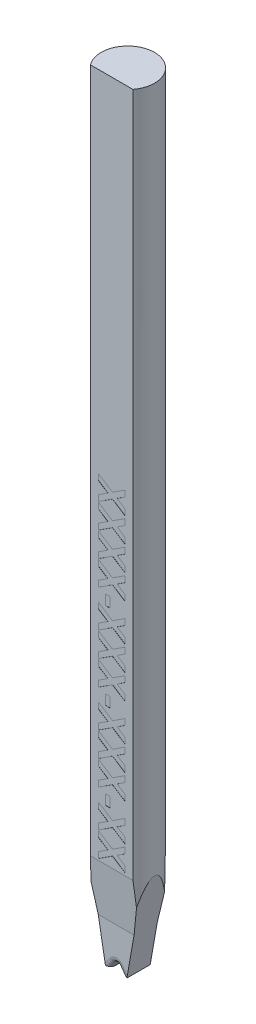
SolidWorks part; units mm, degrees
ref_plane "Ebene vorne" through (0, 0, 0) normal (0, 0, 1) x (1, 0, 0)
ref_plane "Ebene oben" through (0, 0, 0) normal (0, 1, 0) x (1, 0, 0)
ref_plane "Ebene rechts" through (0, 0, 0) normal (1, 0, 0) x (0, 0, -1)
sketch "sketch_TL_cutting" plane through (0, 0, 0) normal (0, 1, 0) x (1, 0, 0)
  circle A0 centre (0, 0) radius 0.9969
extrude "TL_cutting" add sketch "sketch_TL_cutting" along normal blind 29.0068
sketch "sketch_TDF_grinding" plane through (0, 0, 0) normal (0, 1, 0) x (1, 0, 0)
  line L0 (0, 0) -> (0, -0.6033) construction
  line L1 (-1.007, -2.6171) -> (1.007, -2.6171)
  line L2 (-1.007, -2.6171) -> (-1.007, -0.6033)
  line L3 (-1.007, -0.6033) -> (1.007, -0.6032)
  line L4 (1.007, -2.6171) -> (1.007, -0.6032)
  circle A1 centre (0, 0) radius 0.9969 construction
  point P9 (0, -2.6172)
  dimension "TD_2Offset_X" = 2.0139
  dimension "TD_2Offset_Z" = 2.0139
extrude "TDF_grinding" cut sketch "sketch_TDF_grinding" along normal through all
sketch "sketch_engraving" plane through (0, 0, 0.6033) normal (0, 0, 1) x (1, 0, 0)
  line L0 (0.7937, 29.0068) -> (-0.7937, 29.0068) construction
  line L6 (-0.7937, 0) -> (0.7937, 0) construction
  line L7 (0, 0) -> (0, 15.9537) construction
  line L8 (-0.5, 15.9537) -> (-0.5, 0) construction
  text T0 "XXXX-XXX-XXX-XX" font "Arial" height 1
  dimension "D2" = 0.5
  dimension "EngravingStart" = 13.0531
extrude "engraving" cut sketch "sketch_engraving" against normal blind 0.005
sketch "sketch_VW_VR_grinding" plane through (0, 0, 0) normal (0, 0, 1) x (1, 0, 0)
  line L0 (-0.9919, -0.01) -> (-0.9919, 1.509)
  line L1 (0.9919, -0.01) -> (0.9919, 1.509)
  line L2 (-0.9919, 0) -> (0.9919, 0) construction
  line L3 (-1.007, 1.514) -> (-0.9969, 1.514)
  line L4 (0.9969, 1.514) -> (1.007, 1.514)
  line L5 (-1.007, 1.514) -> (-1.007, -0.01)
  line L6 (-1.007, -0.01) -> (-0.9919, -0.01)
  line L7 (0.9919, -0.01) -> (1.007, -0.01)
  line L8 (1.007, -0.01) -> (1.007, 1.514)
  line L9 (-0.9969, 1.514) -> (-0.9969, 1.509) construction
  line L10 (-0.9919, 1.509) -> (-0.9969, 1.509) construction
  line L11 (0.9919, 1.509) -> (0.9969, 1.509) construction
  line L12 (0.9969, 1.514) -> (0.9969, 1.509) construction
  arc A0 (-0.9969, 1.514) -> (-0.9919, 1.509) centre (-0.9969, 1.509) cw
  arc A2 (0.9919, 1.509) -> (0.9969, 1.514) centre (0.9969, 1.509) cw
  dimension "D1" = 0.01
  dimension "D4" = 2.0139
extrude "VW_VR_grinding" cut sketch "sketch_VW_VR_grinding" against normal blind 1.007 and the other way blind 1.007
sketch "sketch_ISA_grinding" plane through (0, 0, 0) normal (0, 0, 1) x (1, 0, 0)
  line L0 (-0.4001, 0) -> (-1.007, 3.4419)
  line L4 (1.007, 3.4419) -> (0.4001, 0)
  line L5 (0.4001, 0) -> (-0.4001, 0)
  line L6 (0, 0) -> (0, 30.49) construction
  line L7 (-1.007, 3.4419) -> (-1.007, -0.01)
  line L12 (-1.007, -0.01) -> (1.007, -0.01)
  line L13 (1.007, -0.01) -> (1.007, 3.4419)
  line L14 (-0.9919, -0.01) -> (-0.9919, 1.509) construction
  point P3 (-0.9919, 3.3568)
  dimension "ISA" = 20
  dimension "TD_2Offset" = 2.0139
  dimension "Offset" = 0.01
extrude "ISA_grinding" cut sketch "sketch_ISA_grinding" against normal blind 1.007 and the other way blind 1.007
sketch "sketch_pre_FRX_BRX" plane through (0, 0, 0) normal (1, 0, 0) x (0, 0, -1)
  line L0 (0.9969, -0.01) -> (0.9969, 3.9152) construction
  line L1 (-0.6033, -0.01) -> (-0.6033, 1.514) construction
  line L2 (-0.4356, -0.01) -> (-0.4356, 1.514)
  line L3 (-0.4356, 1.514) -> (-1.007, 1.514)
  line L4 (-1.007, 1.514) -> (-1.007, -0.01)
  line L5 (-1.007, -0.01) -> (-0.4356, -0.01)
  line L6 (0.4356, -0.01) -> (0.4356, 1.514)
  line L7 (0.4356, 1.514) -> (1.0069, 1.514)
  line L8 (1.0069, 1.514) -> (1.007, -0.01)
  line L9 (1.007, -0.01) -> (0.4356, -0.01)
  dimension "D3" = 0.01
  dimension "D4" = 1.524
  dimension "D5" = 2.0139
  dimension "D6" = 0.8712
  dimension "D2" = 0.01
  dimension "D7" = 1.4326
extrude "pre_FRX_BRX" cut sketch "sketch_pre_FRX_BRX" against normal blind 1.007 and the other way blind 1.007
sketch "sketch_contour_V-Groove" plane through (0, 0, 0) normal (1, 0, 0) x (0, 0, -1)
  line L0 (-0.6033, 0.254) -> (0, 0.254)
  line L1 (0, 0.254) -> (0.9969, 0.254)
  line L2 (0.9969, -0.8411) -> (0.9969, 1.3178) construction
  line L3 (-0.6033, -0.9209) -> (-0.6033, 1.9363) construction
  line L4 (-0.6033, 0) -> (0.997, 0) construction
  line L5 (0.4356, 0) -> (0.4356, 0.254) construction
  line L6 (-0.4356, 0) -> (-0.4356, 0.254) construction
  dimension "D1" = 0
ref_plane "front" through (0, 0, 0.6033) normal (0, 0, 1) x (1, 0, 0)
ref_plane "back" through (0, 0, -0.9969) normal (0, 0, 1) x (1, 0, 0)
sketch "sketch_section_V-Groove" plane through (0, 0, 0.6033) normal (0, 0, 1) x (1, 0, 0)
  line L0 (-1.9982, -2.54) -> (-0.0659, 0.2197)
  line L2 (0.0659, 0.2197) -> (1.9982, -2.54)
  line L3 (-1.9982, -2.54) -> (1.9982, -2.54)
  line L4 (0, -2.54) -> (0, 0.254) construction
  line L5 (-0.2197, 0) -> (0.2197, 0) construction
  arc A0 (0.0659, 0.2197) -> (-0.0659, 0.2197) centre (0, 0.1736) ccw
  dimension "GA" = 70
sweep "V-Groove_EDM" cut profiles "sketch_section_V-Groove" path "sketch_contour_V-Groove"
fillet "FR_EDM" radius 0.2007 3 edges at (0.1428, 0.1099, 0.4356) (0, 0.254, 0.4356) (-0.1428, 0.1099, 0.4356)
fillet "BR_EDM" radius 0.2007 3 edges at (0.1428, 0.1099, -0.4356) (0, 0.254, -0.4356) (-0.1428, 0.1099, -0.4356)
sketch "sketch_FA_BA_grinding" plane through (0, 0, 0) normal (1, 0, 0) x (0, 0, -1)
  line L2 (1.9969, 19.3702) -> (1.997, -0.1)
  line L3 (1.997, -0.1) -> (0.4356, -0.1)
  line L5 (0.4356, -0.1) -> (0.4356, 1.524)
  line L6 (0.4356, 1.524) -> (1.9969, 19.3702)
  line L7 (0.9969, -0.1) -> (0.9969, 7.9401) construction
  line L8 (-0.6032, 3.4401) -> (-0.6032, -0.1) construction
  line L9 (-2.2816, 22.6236) -> (-0.4356, 1.524)
  line L10 (-0.4356, 1.524) -> (-0.4356, -0.1)
  line L11 (-0.4356, -0.1) -> (-2.2816, -0.1)
  line L12 (-2.2816, -0.1) -> (-2.2816, 22.6236)
  line L13 (-0.4356, 1.524) -> (0.4356, 1.524) construction
  dimension "D4" = 1
  dimension "D1" = 0.1
  dimension "FA" = 5
  dimension "BA" = 5
extrude "FA_BA_grinding" cut sketch "sketch_FA_BA_grinding" against normal blind 1.007 and the other way blind 1.007
sketch "sketch_groove_dimensions" plane through (0, 0, 0) normal (1, 0, 0) x (0, 0, -1)
  line L0 (-0.235, 0.254) -> (0.235, 0.254)
  line L1 (-0.4356, 0) -> (-0.4356, 0.4547) construction
  line L2 (0.9969, 0) -> (0.9969, 0.4166) construction
  line L3 (0.4356, 0) -> (0.4356, 0.4547) construction
  line L4 (-0.6033, 0) -> (-0.6033, 0.3999) construction
  arc A0 (0.235, 0.254) -> (0.4356, 0.4547) centre (0.235, 0.4547) ccw
  arc A1 (-0.235, 0.254) -> (-0.4356, 0.4547) centre (-0.235, 0.4547) cw
equation "\"_Offset\"=0.01mm"
equation "\"TL\"=29.0068mm"
equation "\"TD\"=1.9939mm"
equation "\"TDF\"=1.6002mm"
equation "\"BA\"=5deg"
equation "\"ISA\"=20deg"
equation "\"FA\"=5deg"
equation "\"GR\"=0.08128mm"
equation "\"GA\"=70deg"
equation "\"GD\"=0.254mm"
equation "\"FL\"=0.87122mm"
equation "\"F\"=0.4699mm"
equation "\"FX\"=0.16764mm"
equation "\"B\"=0.43942mm"
equation "\"VW\"=0mm"
equation "\"cleaned_VR\"= IIF ( \"VR\" > 0 , \"VR\" , \"E\" - \"_Offset\" )"
equation "\"cleaned_VW\"= IIF ( \"VW\" > 0 , \"VW\" , \"TD\" - \"_Offset\" )"
equation "\"back_edge\"= \"TD\" / 2 - \"X\""
equation "\"side_edge_Offset\"= \"TD\" / 2 + \"_Offset\""
equation "\"TD@sketch_TL_cutting\"=\"TD\""
equation "\"TL@TL_cutting\"=\"TL\""
equation "\"TDF@sketch_TDF_grinding\"=\"TDF\""
equation "\"TD_2Offset_X@sketch_TDF_grinding\"=\"TD\"+2*\"_Offset\""
equation "\"TD_2Offset_Z@sketch_TDF_grinding\"=\"TD\"+2*\"_Offset\""
equation "\"TL_Offset\"= \"TL\" + \"_Offset\""
equation "\"ISA@sketch_ISA_grinding\"=\"ISA\""
equation "\"W@sketch_ISA_grinding\"=\"W\""
equation "\"TD_2Offset@sketch_ISA_grinding\"=\"TD\"+2*\"_Offset\""
equation "\"Offset@sketch_ISA_grinding\"=\"_Offset\""
equation "\"05TD_Offset_posZ@ISA_grinding\"=\"side_edge_Offset\""
equation "\"05TD_Offset_negZ@ISA_grinding\"=\"side_edge_Offset\""
equation "\"E\"=1.524mm"
equation "\"cleaned_X\"= IIF ( \"X\" > 0 , \"X\" , \"TD\" / 2 - \"FL\" / 2 )"
equation "\"FR\"=0.20066mm"
equation "\"BR\"=0.20066mm"
equation "\"D1\"= \"side_edge_Offset\""
equation "\"D2\"= \"side_edge_Offset\""
equation "\"TDF@sketch_FA_BA_grinding\" = \"TDF\""
equation "\"FL@sketch_FA_BA_grinding\"=\"FL\""
equation "\"E@sketch_FA_BA_grinding\" = \"E\""
equation "\"D1@FA_BA_grinding\"=\"side_edge_Offset\""
equation "\"D2@FA_BA_grinding\"=\"side_angle_Offset\""
equation "\"10GD@sketch_section_V-Groove\" = 10 * \"GD\""
equation "\"GA@sketch_section_V-Groove\" = \"GA\""
equation "\"GD@sketch_section_V-Groove\" = \"GD\""
equation "\"B@sketch_section_V-Groove\" = \"B\""
equation "\"GD@sketch_contour_V-Groove\" = \"GD\""
equation "\"cleaned_FRX\"= IIF ( \"FRX\" > 0 , \"FRX\" , \"FR\" )"
equation "\"cleaned_BRX\"= IIF ( \"BRX\" > 0 , \"BRX\" , \"BR\" )"
equation "\"FL_groove_angle\"=0deg"
equation "\"D3@sketch_pre_FRX_BRX\" = \"_Offset\""
equation "\"D4@sketch_pre_FRX_BRX\" = \"E\""
equation "\"D5@sketch_pre_FRX_BRX\" = 2 * \"side_edge_Offset\""
equation "\"D6@sketch_pre_FRX_BRX\" = \"FL\" + ( \"FR\" - \"cleaned_FRX\" ) + ( \"BR\" - \"cleaned_BRX\" )"
equation "\"TD/2@sketch_pre_FRX_BRX\" = \"TD\" / 2"
equation "\"TDF@sketch_pre_FRX_BRX\" = \"TDF\""
equation "\"D2@sketch_pre_FRX_BRX\" = \"_Offset\""
equation "\"D1@pre_FRX_BRX\" = \"side_edge_Offset\""
equation "\"D2@pre_FRX_BRX\" = \"side_edge_Offset\""
equation "\"D1@BR_EDM\"=\"BR\""
equation "\"TD/2@sketch_FA_BA_grinding\" = \"TD\" / 2"
equation "\"TD/2@sketch_contour_V-Groove\" = \"TD\" / 2"
equation "\"TDF@sketch_contour_V-Groove\" = \"TDF\""
equation "\"D1@sketch_contour_V-Groove\"=\"FL_groove_angle\""
equation "\"FL@sketch_contour_V-Groove\"=\"FL\""
equation "\"FL/2@sketch_contour_V-Groove\" = \"FL\" / 2"
equation "\"D1@FR_EDM\"=\"FR\""
equation "\"D1@sketch_VW_VR_grinding\" = \"_Offset\""
equation "\"D4@sketch_VW_VR_grinding\" = 2 * \"side_edge_Offset\""
equation "\"VR@sketch_VW_VR_grinding\" = \"cleaned_VR\""
equation "\"VW@sketch_VW_VR_grinding\"=\"cleaned_VW\""
equation "\"D1@VW_VR_grinding\" = \"side_edge_Offset\""
equation "\"D2@VW_VR_grinding\" = \"side_edge_Offset\""
equation "\"X\"=0mm"
equation "\"VR\"=0mm"
equation "\"W\"=0.8001mm"
equation "\"VW_radius\"= \"cleaned_VW\" / 10"
equation "\"VW_radius_cleaned\"= IIF ( \"VW\" > 0 , \"VW_radius\" , \"_Offset\" / 2 )"
equation "\"D2@sketch_VW_VR_grinding\"=\"VW_radius_cleaned\""
equation "\"FRX\"=0mm"
equation "\"BRX\"=0mm"
equation "\"FA@sketch_FA_BA_grinding\" = \"FA\""
equation "\"D4@sketch_FA_BA_grinding\"=\"_Offset\"*100"
equation "\"BA@sketch_FA_BA_grinding\" = \"BA\""
equation "\"D1@sketch_groove_dimensions\" = \"TD\" / 2"
equation "\"FL@sketch_groove_dimensions\" = \"FL\""
equation "\"FR@sketch_groove_dimensions\" = \"FR\""
equation "\"BR@sketch_groove_dimensions\" = \"BR\""
equation "\"FRX@sketch_groove_dimensions\" = \"cleaned_FRX\""
equation "\"BRX@sketch_groove_dimensions\" = \"cleaned_BRX\""
equation "\"GD@sketch_groove_dimensions\" = \"GD\""
equation "\"cleaned_FX\"= IIF ( \"FX\" > 0 , \"FX\" , \"TDF\" - ( \"TD\" + \"FL\" ) / 2 )"
equation "\"D7@sketch_pre_FRX_BRX\"=\"TDF\"-\"cleaned_FX\"-(\"FR\"-\"cleaned_FRX\")"
equation "\"FX@sketch_contour_V-Groove\" = \"cleaned_FX\""
equation "\"FX@sketch_FA_BA_grinding\" = \"cleaned_FX\""
equation "\"TDF@sketch_groove_dimensions\" = \"TDF\""
equation "\"FX@sketch_groove_dimensions\" = \"cleaned_FX\""
equation "\"EngravingStart\" = \"TL\" * 0.45"
equation "\"EngravingStart@sketch_engraving\" = \"EngravingStart\""
